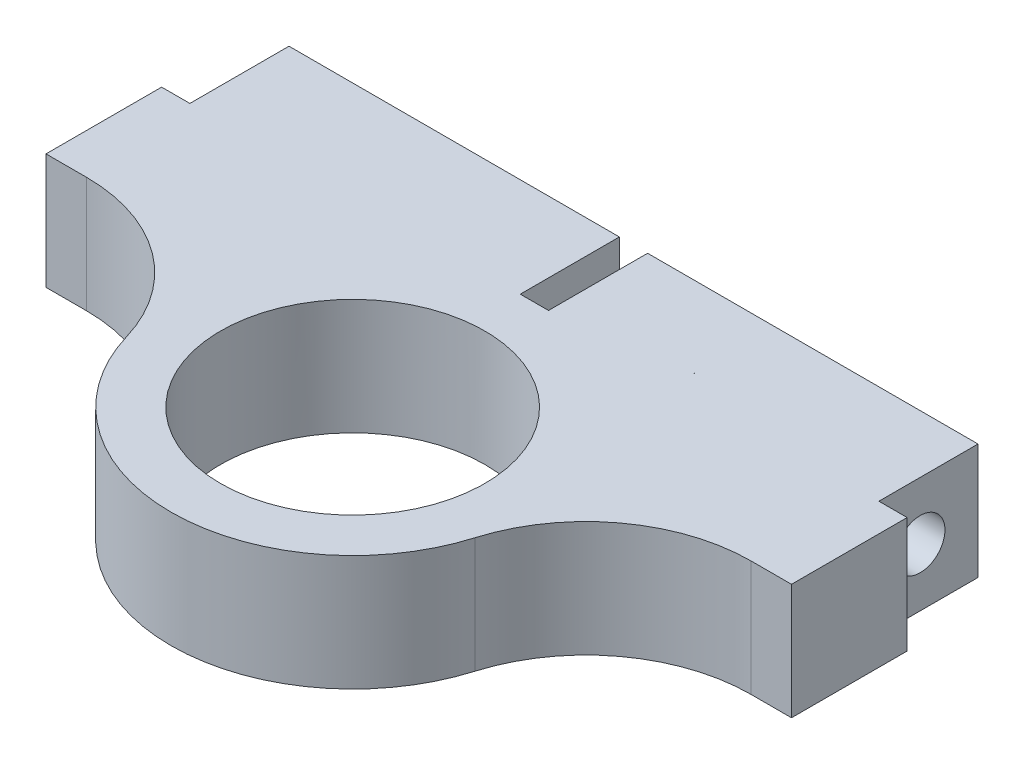
SolidWorks part; units mm, degrees
ref_plane "Front Plane" through (0, 0, 0) normal (0, 0, 1) x (1, 0, 0)
ref_plane "Top Plane" through (0, 0, 0) normal (0, 1, 0) x (1, 0, 0)
ref_plane "Right Plane" through (0, 0, 0) normal (1, 0, 0) x (0, 0, -1)
sketch "Sketch1" plane through (0, 0, 0) normal (0, 1, 0) x (1, 0, 0)
  line L0 (0, 0) -> (45.13, 0)
  line L1 (0, 0) -> (22.565, 0)
  line L2 (22.565, 0) -> (22.565, -8)
  line L3 (0, 0) -> (0, 7)
  line L4 (0, 7) -> (45.13, 7)
  line L5 (45.13, 7) -> (45.13, 0)
  circle A2 centre (22.565, -8) radius 11
  circle A3 centre (22.565, -8) radius 8
extrude "Boss-Extrude1" add sketch "Sketch1" along normal blind 10 contours A2 L0 L5 L4 L3 | L0 A2 L1 | A3 L1 A2 L0
sketch "Sketch2" plane through (0, 10, 0) normal (0, 1, 0) x (1, 0, 0)
  line L0 (0, 7) -> (1.71, 7)
  line L1 (0, 7) -> (45.13, 7) construction
  line L2 (1.71, 7) -> (21.71, 7)
  line L3 (21.71, 7) -> (23.42, 7)
  line L4 (23.42, 7) -> (43.42, 7)
  line L5 (43.42, 7) -> (45.13, 7)
  line L6 (0, 0) -> (0, 3)
  line L7 (0, 0) -> (0, 7) construction
  line L8 (0, 3) -> (45.13, 3)
  line L9 (45.13, 7) -> (45.13, 0) construction
  line L10 (1.71, 7) -> (1.71, 3)
  line L11 (1.71, 3) -> (21.71, 3)
  line L12 (21.71, 3) -> (21.71, 7)
  line L13 (23.42, 7) -> (23.42, 3)
  line L14 (23.42, 3) -> (43.42, 3)
  line L15 (43.42, 3) -> (43.42, 7)
  line L16 (0, 7) -> (0, 3)
  line L17 (45.13, 3) -> (45.13, 7)
  line M7 (45.13, 0) -> (45.13, 7)
  line M8 (45.13, 7) -> (0, 7)
  line M9 (0, 7) -> (0, 0)
extrude "Cut-Extrude1" cut sketch "Sketch2" against normal blind 10 contours L10 L8 M8 M9 | L13 L12 L8 M8 | L15 L8 M7 M8
sketch "Sketch3" plane through (0, 0, -7) normal (0, 0, -1) x (-1, 0, 0)
  line L0 (-43.42, 0) -> (-23.42, 0) construction
  line L1 (-23.42, 0) -> (-23.42, 10) construction
  line L2 (-23.42, 10) -> (-43.42, 10) construction
  line L3 (-43.42, 10) -> (-43.42, 0) construction
  line L4 (-21.71, 0) -> (-1.71, 0) construction
  line L5 (-1.71, 0) -> (-1.71, 10) construction
  line L6 (-1.71, 10) -> (-21.71, 10) construction
  line L7 (-21.71, 10) -> (-21.71, 0) construction
  line L8 (-43.42, 0) -> (-23.42, 0)
  line L9 (-23.42, 0) -> (-23.42, 10)
  line L10 (-23.42, 10) -> (-43.42, 10)
  line L11 (-43.42, 10) -> (-43.42, 0)
  line L12 (-21.71, 0) -> (-1.71, 0)
  line L13 (-1.71, 0) -> (-1.71, 10)
  line L14 (-1.71, 10) -> (-21.71, 10)
  line L15 (-21.71, 10) -> (-21.71, 0)
extrude "Boss-Extrude2" add sketch "Sketch3" along normal blind 3
sketch "Sketch4" plane through (0, 10, 0) normal (0, 1, 0) x (1, 0, 0)
  line L13 (21.71, 3) -> (21.71, 10)
  line L14 (21.71, 10) -> (1.71, 10)
  line L15 (1.71, 10) -> (1.71, 3)
  line L16 (1.71, 3) -> (0, 3)
  line L17 (0, 3) -> (0, 0)
  line L18 (0, 0) -> (15.0152, 0)
  line L19 (30.1148, 0) -> (45.13, 0)
  line L20 (45.13, 0) -> (45.13, 3)
  line L21 (45.13, 3) -> (43.42, 3)
  line L22 (43.42, 3) -> (43.42, 10)
  line L23 (43.42, 10) -> (23.42, 10)
  line L24 (23.42, 10) -> (23.42, 3)
  line L25 (23.42, 3) -> (21.71, 3)
  line L26 (21.71, 3) -> (21.71, 10)
  line L27 (21.71, 10) -> (1.71, 10)
  line L28 (1.71, 10) -> (1.71, 3)
  line L29 (1.71, 3) -> (0, 3)
  line L30 (0, 3) -> (0, 0)
  line L31 (0, 0) -> (15.0152, 0)
  line L32 (30.1148, 0) -> (45.13, 0)
  line L33 (45.13, 0) -> (45.13, 3)
  line L34 (45.13, 3) -> (43.42, 3)
  line L35 (43.42, 3) -> (43.42, 10)
  line L36 (43.42, 10) -> (23.42, 10)
  line L37 (23.42, 10) -> (23.42, 3)
  line L38 (23.42, 3) -> (21.71, 3)
  arc A4 (15.0152, 0) -> (30.1148, 0) centre (22.565, -8) ccw
  arc A7 (15.0152, 0) -> (30.1148, 0) centre (22.565, -8) ccw
  dimension "D1" = 0
extrude "Cut-Extrude2" cut sketch "Sketch4" against normal blind 3
sketch "Sketch6" plane through (0, 0, -10) normal (0, 0, -1) x (-1, 0, 0)
  line L0 (-23.42, 0) -> (-23.42, 7) construction
  line L1 (-23.42, 7) -> (-43.42, 7) construction
  line L2 (-43.42, 7) -> (-43.42, 0) construction
  line L3 (-43.42, 0) -> (-23.42, 0) construction
  line L4 (-1.71, 0) -> (-1.71, 7) construction
  line L5 (-1.71, 7) -> (-21.71, 7) construction
  line L6 (-21.71, 7) -> (-21.71, 0) construction
  line L7 (-21.71, 0) -> (-1.71, 0) construction
  line L8 (-23.42, 0) -> (-23.42, 7)
  line L9 (-23.42, 7) -> (-43.42, 7)
  line L10 (-43.42, 7) -> (-43.42, 0)
  line L11 (-43.42, 0) -> (-23.42, 0)
  line L12 (-1.71, 0) -> (-1.71, 7)
  line L13 (-1.71, 7) -> (-21.71, 7)
  line L14 (-21.71, 7) -> (-21.71, 0)
  line L15 (-21.71, 0) -> (-1.71, 0)
extrude "Boss-Extrude3" add sketch "Sketch6" along normal blind 2
sketch "Sketch7" plane through (1.71, 0, 0) normal (-1, 0, 0) x (0, 0, 1)
  line L0 (-3, 0) -> (-3, 7)
  line L1 (-3, 7) -> (-3, 3.5)
  line L2 (-3, 3.5) -> (-8.5, 3.5)
  circle A0 centre (-8.5, 3.5) radius 1.5
extrude "Cut-Extrude5" cut sketch "Sketch7" against normal blind 44
sketch "Sketch9" plane through (0, 0, -3) normal (0, 0, -1) x (-1, 0, 0)
  line L4 (-21.71, 7) -> (-23.42, 7)
  line L5 (-23.42, 7) -> (-23.42, 0)
  line L6 (-23.42, 0) -> (-21.71, 0)
  line L7 (-21.71, 0) -> (-21.71, 7)
  line L8 (-21.71, 7) -> (-23.42, 7)
  line L9 (-23.42, 7) -> (-23.42, 0)
  line L10 (-23.42, 0) -> (-21.71, 0)
  line L11 (-21.71, 0) -> (-21.71, 7)
  line L12 (0, 7) -> (-1.71, 7)
  line L13 (-1.71, 7) -> (-1.71, 0)
  line L14 (-1.71, 0) -> (0, 0)
  line L15 (0, 0) -> (0, 7)
  line L16 (0, 7) -> (-1.71, 7)
  line L17 (-1.71, 7) -> (-1.71, 0)
  line L18 (-1.71, 0) -> (0, 0)
  line L19 (0, 0) -> (0, 7)
  line L20 (-43.42, 7) -> (-45.13, 7)
  line L21 (-45.13, 7) -> (-45.13, 0)
  line L22 (-45.13, 0) -> (-43.42, 0)
  line L23 (-43.42, 0) -> (-43.42, 7)
  line L24 (-43.42, 7) -> (-45.13, 7)
  line L25 (-45.13, 7) -> (-45.13, 0)
  line L26 (-45.13, 0) -> (-43.42, 0)
  line L27 (-43.42, 0) -> (-43.42, 7)
  dimension "D1" = 0
  dimension "D2" = 0
  dimension "D3" = 0
extrude "Boss-Extrude4" add sketch "Sketch9" along normal blind 3
sketch "Sketch11" plane through (0, 7, 0) normal (0, 1, 0) x (1, 0, 0)
  line L13 (45.13, 6) -> (43.42, 6)
  line L14 (43.42, 6) -> (43.42, 12)
  line L15 (43.42, 12) -> (23.42, 12)
  line L16 (23.42, 12) -> (23.42, 6)
  line L17 (23.42, 6) -> (21.71, 6)
  line L18 (21.71, 6) -> (21.71, 12)
  line L19 (21.71, 12) -> (1.71, 12)
  line L20 (1.71, 12) -> (1.71, 6)
  line L21 (1.71, 6) -> (0, 6)
  line L22 (0, 6) -> (0, 0)
  line L23 (0, 0) -> (15.0152, 0)
  line L24 (30.1148, 0) -> (45.13, 0)
  line L25 (45.13, 0) -> (45.13, 6)
  line L26 (45.13, 6) -> (43.42, 6)
  line L27 (43.42, 6) -> (43.42, 12)
  line L28 (43.42, 12) -> (23.42, 12)
  line L29 (23.42, 12) -> (23.42, 6)
  line L30 (23.42, 6) -> (21.71, 6)
  line L31 (21.71, 6) -> (21.71, 12)
  line L32 (21.71, 12) -> (1.71, 12)
  line L33 (1.71, 12) -> (1.71, 6)
  line L34 (1.71, 6) -> (0, 6)
  line L35 (0, 6) -> (0, 0)
  line L36 (0, 0) -> (15.0152, 0)
  line L37 (30.1148, 0) -> (45.13, 0)
  line L38 (45.13, 0) -> (45.13, 6)
  circle A0 centre (22.565, -8) radius 8 construction
  circle A1 centre (22.565, -8) radius 8
  arc A4 (15.0152, 0) -> (30.1148, 0) centre (22.565, -8) ccw
  arc A7 (15.0152, 0) -> (30.1148, 0) centre (22.565, -8) ccw
  dimension "D1" = 0
extrude "Cut-Extrude6" cut sketch "Sketch11" against normal blind 1
sketch "Sketch12" plane through (0, 6, 0) normal (0, 1, 0) x (1, 0, 0)
  line L13 (45.13, 0) -> (45.13, 6)
  line L14 (45.13, 6) -> (43.42, 6)
  line L15 (43.42, 6) -> (43.42, 12)
  line L16 (43.42, 12) -> (23.42, 12)
  line L17 (23.42, 12) -> (23.42, 6)
  line L18 (23.42, 6) -> (21.71, 6)
  line L19 (21.71, 6) -> (21.71, 12)
  line L20 (21.71, 12) -> (1.71, 12)
  line L21 (1.71, 12) -> (1.71, 6)
  line L22 (1.71, 6) -> (0, 6)
  line L23 (0, 6) -> (0, 0)
  line L24 (0, 0) -> (15.0152, 0)
  line L25 (30.1148, 0) -> (45.13, 0)
  line L26 (45.13, 0) -> (45.13, 6)
  line L27 (45.13, 6) -> (43.42, 6)
  line L28 (43.42, 6) -> (43.42, 12)
  line L29 (43.42, 12) -> (23.42, 12)
  line L30 (23.42, 12) -> (23.42, 6)
  line L31 (23.42, 6) -> (21.71, 6)
  line L32 (21.71, 6) -> (21.71, 12)
  line L33 (21.71, 12) -> (1.71, 12)
  line L34 (1.71, 12) -> (1.71, 6)
  line L35 (1.71, 6) -> (0, 6)
  line L36 (0, 6) -> (0, 0)
  line L37 (0, 0) -> (15.0152, 0)
  line L38 (30.1148, 0) -> (45.13, 0)
  arc A4 (15.0152, 0) -> (30.1148, 0) centre (22.565, -8) ccw
  arc A7 (15.0152, 0) -> (30.1148, 0) centre (22.565, -8) ccw
  dimension "D1" = 0
extrude "Boss-Extrude6" add sketch "Sketch12" along normal blind 1
sketch "Sketch13" plane through (0, 6, 0) normal (0, -1, 0) x (1, 0, 0)
  circle A1 centre (22.565, 8) radius 8
  circle A2 centre (22.565, 8) radius 8
  dimension "D1" = 0
extrude "Boss-Extrude7" add sketch "Sketch13" along normal up to surface (6 mm away) up to face at (22.565, 0, -4.6429)
sketch "Sketch14" plane through (0, 0, 0) normal (0, -1, 0) x (1, 0, 0)
  circle A0 centre (22.565, 8) radius 8
extrude "Boss-Extrude8" add sketch "Sketch14" along normal blind 40
sketch "Sketch15" plane through (0, -40, 0) normal (0, -1, 0) x (1, 0, 0)
  circle A0 centre (22.565, 8) radius 7.5
extrude "Boss-Extrude9" add sketch "Sketch15" along normal blind 30
sketch "Sketch16" plane through (0, 0, 0) normal (0, -1, 0) x (1, 0, 0)
  line L13 (43.42, -12) -> (43.42, -6)
  line L14 (43.42, -6) -> (45.13, -6)
  line L15 (45.13, -6) -> (45.13, 0)
  line L16 (45.13, 0) -> (30.1148, 0)
  line L17 (15.0152, 0) -> (0, 0)
  line L18 (0, 0) -> (0, -6)
  line L19 (0, -6) -> (1.71, -6)
  line L20 (1.71, -6) -> (1.71, -12)
  line L21 (1.71, -12) -> (21.71, -12)
  line L22 (21.71, -12) -> (21.71, -6)
  line L23 (21.71, -6) -> (23.42, -6)
  line L24 (23.42, -6) -> (23.42, -12)
  line L25 (23.42, -12) -> (43.42, -12)
  line L26 (43.42, -12) -> (43.42, -6)
  line L27 (43.42, -6) -> (45.13, -6)
  line L28 (45.13, -6) -> (45.13, 0)
  line L29 (45.13, 0) -> (30.1148, 0)
  line L30 (15.0152, 0) -> (0, 0)
  line L31 (0, 0) -> (0, -6)
  line L32 (0, -6) -> (1.71, -6)
  line L33 (1.71, -6) -> (1.71, -12)
  line L34 (1.71, -12) -> (21.71, -12)
  line L35 (21.71, -12) -> (21.71, -6)
  line L36 (21.71, -6) -> (23.42, -6)
  line L37 (23.42, -6) -> (23.42, -12)
  line L38 (23.42, -12) -> (43.42, -12)
  arc A4 (30.1148, 0) -> (15.0152, 0) centre (22.565, 8) ccw
  arc A7 (30.1148, 0) -> (15.0152, 0) centre (22.565, 8) ccw
  dimension "D1" = 0
extrude "Boss-Extrude10" add sketch "Sketch16" along normal blind 6.5
sketch "Sketch17" plane through (0, -70, 0) normal (0, -1, 0) x (1, 0, 0)
  circle A0 centre (22.565, 8) radius 7
  circle A1 centre (22.565, 8) radius 15.7734
extrude "Cut-Extrude7" cut sketch "Sketch17" against normal up to surface (30 mm away) up to face at (22.565, -40, 0.5)
sketch "Sketch18" plane through (0, -70, 0) normal (0, -1, 0) x (1, 0, 0)
  circle A0 centre (22.565, 8) radius 7.1
extrude "Boss-Extrude11" add sketch "Sketch18" against normal up to surface (30 mm away) contours A0 up to face at (22.565, -40, 0)
sketch "Sketch19" plane through (0, -70, 0) normal (0, -1, 0) x (1, 0, 0)
  circle A0 centre (22.565, 8) radius 7.2
extrude "Boss-Extrude12" add sketch "Sketch19" against normal up to surface (30 mm away) up to face at (22.565, -40, 0.9)
sketch "Sketch20" plane through (0, -70, 0) normal (0, -1, 0) x (1, 0, 0)
  circle A0 centre (22.565, 8) radius 7.15
  circle A1 centre (22.565, 8) radius 12.8107
extrude "Cut-Extrude8" cut sketch "Sketch20" against normal up to surface (30 mm away) up to face at (22.565, -40, 0.8)
sketch "Sketch21" plane through (0, -70, 0) normal (0, -1, 0) x (1, 0, 0)
  circle A1 centre (22.565, 8) radius 7.15
  circle A2 centre (22.565, 8) radius 7.15
  dimension "D1" = 0
extrude "Cut-Extrude9" cut sketch "Sketch21" against normal blind 10
sketch "Sketch22" plane through (0, -40, 0) normal (0, -1, 0) x (1, 0, 0)
  circle A0 centre (22.565, 8) radius 7.15 construction
  circle A1 centre (22.565, 8) radius 8 construction
  circle A2 centre (22.565, 8) radius 7.15
  circle A3 centre (22.565, 8) radius 8
extrude "Cut-Extrude10" cut sketch "Sketch22" against normal blind 10
sketch "Sketch25" plane through (0, 7, 0) normal (0, 1, 0) x (1, 0, 0)
  line L0 (0, 6) -> (0, 3)
  line L1 (0, 6) -> (0, 0) construction
  line L2 (0, 3) -> (45.13, 3)
  line L3 (45.13, 0) -> (45.13, 6) construction
  line L4 (1.71, 6) -> (1.71, 3)
  line L5 (21.71, 6) -> (21.71, 3)
  line L6 (23.42, 6) -> (23.42, 3)
  line L7 (43.42, 6) -> (43.42, 3)
  line L8 (0, 6) -> (45.13, 6)
  line L9 (45.13, 6) -> (45.13, 3)
  line L10 (1.71, 12) -> (1.71, 9)
  line L11 (1.71, 12) -> (1.71, 6) construction
  line L12 (1.71, 9) -> (43.42, 9)
  line L13 (43.42, 6) -> (43.42, 12) construction
  line L14 (43.42, 9) -> (43.42, 12)
  line L15 (43.42, 12) -> (1.71, 12)
  circle A0 centre (22.565, -8) radius 8
  line M2 (45.13, 0) -> (45.13, 6)
  line M3 (45.13, 6) -> (43.42, 6)
  line M4 (43.42, 6) -> (43.42, 12)
  line M5 (43.42, 12) -> (23.42, 12)
  line M6 (23.42, 12) -> (23.42, 6)
  line M7 (23.42, 6) -> (21.71, 6)
  line M8 (21.71, 6) -> (21.71, 12)
  line M9 (21.71, 12) -> (1.71, 12)
  line M10 (1.71, 12) -> (1.71, 6)
  line M11 (1.71, 6) -> (0, 6)
  line M12 (0, 6) -> (0, 0)
extrude "Cut-Extrude13" cut sketch "Sketch25" against normal blind 21 contours L4 L2 M11 M12 | L12 M10 M8 M9 | L12 M6 M4 M5 | L6 L5 L2 M7 | L7 L2 M3 M2
sketch "Sketch26" plane through (1.71, 0, 0) normal (-1, 0, 0) x (0, 0, 1)
  line L0 (-3, 7) -> (-6, 7)
  line L1 (-9, 7) -> (-3, 7) construction
  line L2 (-9, 7) -> (-9, -6.5)
  circle A0 centre (-8.5, 3.5) radius 1.5
  arc M7 (-9, 4.9142) -> (-9, 2.0858) centre (-8.5, 3.5) cw
extrude "Boss-Extrude13" add sketch "Sketch26" against normal up to surface (20 mm away) contours L2 M7 up to face at (21.71, 1.3333, -6.6667)
sketch "Sketch27" plane through (43.42, 0, 0) normal (1, 0, 0) x (0, 0, -1)
  line L0 (9, 7) -> (9, -6.5)
  circle A1 centre (8.5, 3.5) radius 1.5
  arc M7 (9, 2.0858) -> (9, 4.9142) centre (8.5, 3.5) cw
extrude "Boss-Extrude14" add sketch "Sketch27" against normal up to surface (20 mm away) contours L0 M7 up to face at (23.42, 1.3333, -6.6667)
sketch "Sketch28" plane through (1.71, 0, 0) normal (-1, 0, 0) x (0, 0, 1)
  line L2 (-3, 7) -> (-3, 3.5)
  line L3 (-3, -6.5) -> (-3, 7) construction
  line L4 (-3, 3.5) -> (-5.5, 3.5)
  circle A0 centre (-5.5, 3.5) radius 1.5
extrude "Cut-Extrude14" cut sketch "Sketch28" against normal blind 50
sketch "Sketch29" plane through (0, 0, 0) normal (0, 0, 1) x (1, 0, 0)
  line L0 (0, 7) -> (0, -6.5)
  line L1 (0, -6.5) -> (45.13, -6.5)
  line L2 (45.13, -6.5) -> (45.13, 7)
  line L3 (45.13, 7) -> (0, 7)
extrude "Boss-Extrude15" add sketch "Sketch29" along normal blind 4
fillet "Fillet1" radius 10 2 edges at (12.318, 0.25, 4) (32.812, 0.25, 4)
fillet "Fillet2" radius 2 1 edges at (22.565, -6.5, 0)
sketch "Sketch30" plane through (0, -6.5, 0) normal (0, -1, 0) x (1, 0, 0)
  line L13 (45.13, 4) -> (42.6896, 4)
  line L14 (2.4404, 4) -> (0, 4)
  line L15 (0, 4) -> (0, -3)
  line L16 (0, -3) -> (1.71, -3)
  line L17 (1.71, -3) -> (1.71, -9)
  line L18 (1.71, -9) -> (21.71, -9)
  line L19 (21.71, -9) -> (21.71, -3)
  line L20 (21.71, -3) -> (23.42, -3)
  line L21 (23.42, -3) -> (23.42, -9)
  line L22 (23.42, -9) -> (43.42, -9)
  line L23 (43.42, -9) -> (43.42, -3)
  line L24 (43.42, -3) -> (45.13, -3)
  line L25 (45.13, -3) -> (45.13, 4)
  line L26 (45.13, 4) -> (42.6896, 4)
  line L27 (2.4404, 4) -> (0, 4)
  line L28 (0, 4) -> (0, -3)
  line L29 (0, -3) -> (1.71, -3)
  line L30 (1.71, -3) -> (1.71, -9)
  line L31 (1.71, -9) -> (21.71, -9)
  line L32 (21.71, -9) -> (21.71, -3)
  line L33 (21.71, -3) -> (23.42, -3)
  line L34 (23.42, -3) -> (23.42, -9)
  line L35 (23.42, -9) -> (43.42, -9)
  line L36 (43.42, -9) -> (43.42, -3)
  line L37 (43.42, -3) -> (45.13, -3)
  line L38 (45.13, -3) -> (45.13, 4)
  arc A3 (33.1065, 11.1429) -> (42.6896, 4) centre (42.6896, 14) ccw
  arc A4 (33.1065, 11.1429) -> (12.0235, 11.1429) centre (22.565, 8) ccw
  arc A5 (2.4404, 4) -> (12.0235, 11.1429) centre (2.4404, 14) ccw
  arc A6 (33.1065, 11.1429) -> (42.6896, 4) centre (42.6896, 14) ccw
  arc A7 (33.1065, 11.1429) -> (12.0235, 11.1429) centre (22.565, 8) ccw
  arc A8 (2.4404, 4) -> (12.0235, 11.1429) centre (2.4404, 14) ccw
  dimension "D1" = 0
extrude "Cut-Extrude15" cut sketch "Sketch30" along normal blind 59
sketch "Sketch32" plane through (0, -6.5, 0) normal (0, -1, 0) x (1, 0, 0)
  line L13 (45.13, 4) -> (42.6896, 4)
  line L14 (2.4404, 4) -> (0, 4)
  line L15 (0, 4) -> (0, -3)
  line L16 (0, -3) -> (1.71, -3)
  line L17 (1.71, -3) -> (1.71, -9)
  line L18 (1.71, -9) -> (21.71, -9)
  line L19 (21.71, -9) -> (21.71, -3)
  line L20 (21.71, -3) -> (23.42, -3)
  line L21 (23.42, -3) -> (23.42, -9)
  line L22 (23.42, -9) -> (43.42, -9)
  line L23 (43.42, -9) -> (43.42, -3)
  line L24 (43.42, -3) -> (45.13, -3)
  line L25 (45.13, -3) -> (45.13, 4)
  line L26 (45.13, 4) -> (42.6896, 4)
  line L27 (2.4404, 4) -> (0, 4)
  line L28 (0, 4) -> (0, -3)
  line L29 (0, -3) -> (1.71, -3)
  line L30 (1.71, -3) -> (1.71, -9)
  line L31 (1.71, -9) -> (21.71, -9)
  line L32 (21.71, -9) -> (21.71, -3)
  line L33 (21.71, -3) -> (23.42, -3)
  line L34 (23.42, -3) -> (23.42, -9)
  line L35 (23.42, -9) -> (43.42, -9)
  line L36 (43.42, -9) -> (43.42, -3)
  line L37 (43.42, -3) -> (45.13, -3)
  line L38 (45.13, -3) -> (45.13, 4)
  arc A3 (33.1065, 11.1429) -> (42.6896, 4) centre (42.6896, 14) ccw
  arc A4 (33.1065, 11.1429) -> (12.0235, 11.1429) centre (22.565, 8) ccw
  arc A5 (2.4404, 4) -> (12.0235, 11.1429) centre (2.4404, 14) ccw
  arc A6 (33.1065, 11.1429) -> (42.6896, 4) centre (42.6896, 14) ccw
  arc A7 (33.1065, 11.1429) -> (12.0235, 11.1429) centre (22.565, 8) ccw
  arc A8 (2.4404, 4) -> (12.0235, 11.1429) centre (2.4404, 14) ccw
  dimension "D1" = 0
extrude "Cut-Extrude16" cut sketch "Sketch32" against normal blind 6.5
sketch "Sketch33" plane through (0, 7, 0) normal (0, 1, 0) x (1, 0, 0)
  circle A0 centre (22.565, -8) radius 8
extrude "Cut-Extrude17" cut sketch "Sketch33" against normal blind 19.5
